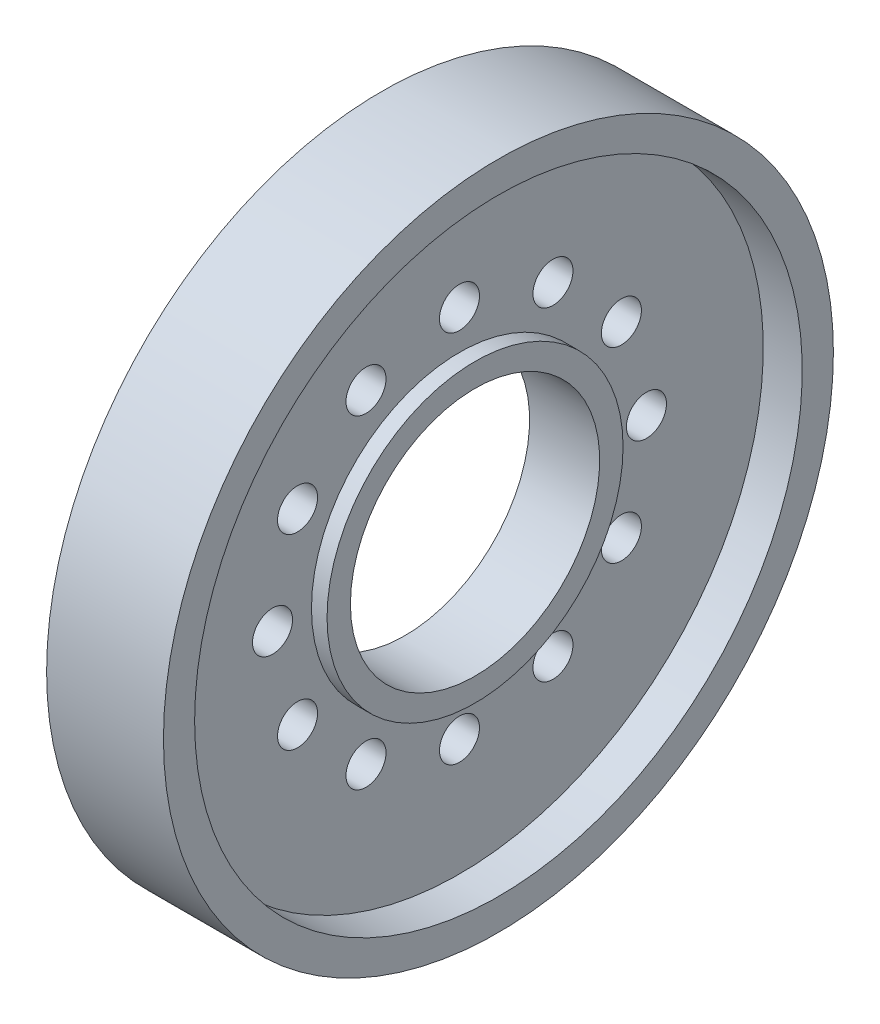
SolidWorks part; units mm, degrees
ref_plane "Front Plane" through (0, 0, 0) normal (0, 0, 1) x (1, 0, 0)
ref_plane "Top Plane" through (0, 0, 0) normal (0, 1, 0) x (1, 0, 0)
ref_plane "Right Plane" through (0, 0, 0) normal (1, 0, 0) x (0, 0, -1)
sketch "Sketch1" plane through (0, 0, 0) normal (0, 0, 1) x (1, 0, 0)
  line L0 (-31.2934, 0) -> (61.3596, 0) construction
  line L1 (-9.525, 54.61) -> (9.525, 54.61)
  line L2 (9.525, 54.61) -> (9.525, 49.53)
  line L3 (9.525, 49.53) -> (3.175, 49.53)
  line L4 (3.175, 49.53) -> (3.175, 24.13)
  line L6 (-3.175, 24.13) -> (-3.175, 49.53)
  line L7 (-3.175, 49.53) -> (-9.525, 49.53)
  line L8 (-9.525, 49.53) -> (-9.525, 54.61)
  line L9 (-3.175, 24.13) -> (-5.715, 24.13)
  line L10 (-5.715, 24.13) -> (-5.715, 20.32)
  line L11 (-5.715, 20.32) -> (5.715, 20.32)
  line L12 (5.715, 20.32) -> (5.715, 24.13)
  line L13 (5.715, 24.13) -> (3.175, 24.13)
  point P5 (0, 39.37)
  point P12 (0, 54.61)
  dimension "D1" = 54.61
  dimension "D2" = 5.08
  dimension "D3" = 25.4
  dimension "D4" = 6.35
  dimension "D5" = 19.05
  dimension "D6" = 3.81
  dimension "D7" = 2.54
revolve "Revolve1" add sketch "Sketch1" angle 360 about L0
sketch "Sketch2" plane through (3.175, 0, 0) normal (1, 0, 0) x (0, 0, -1)
  circle A0 centre (0, 30.48) radius 3.2639
  dimension "D2" = 6.5278
  dimension "D1" = 30.48
extrude "Cut-Extrude1" cut sketch "Sketch2" against normal through all
pattern_circular "CirPattern1" count 12 over 360 about axis through (0, 0, 0) along (1, 0, 0) of "Cut-Extrude1"
